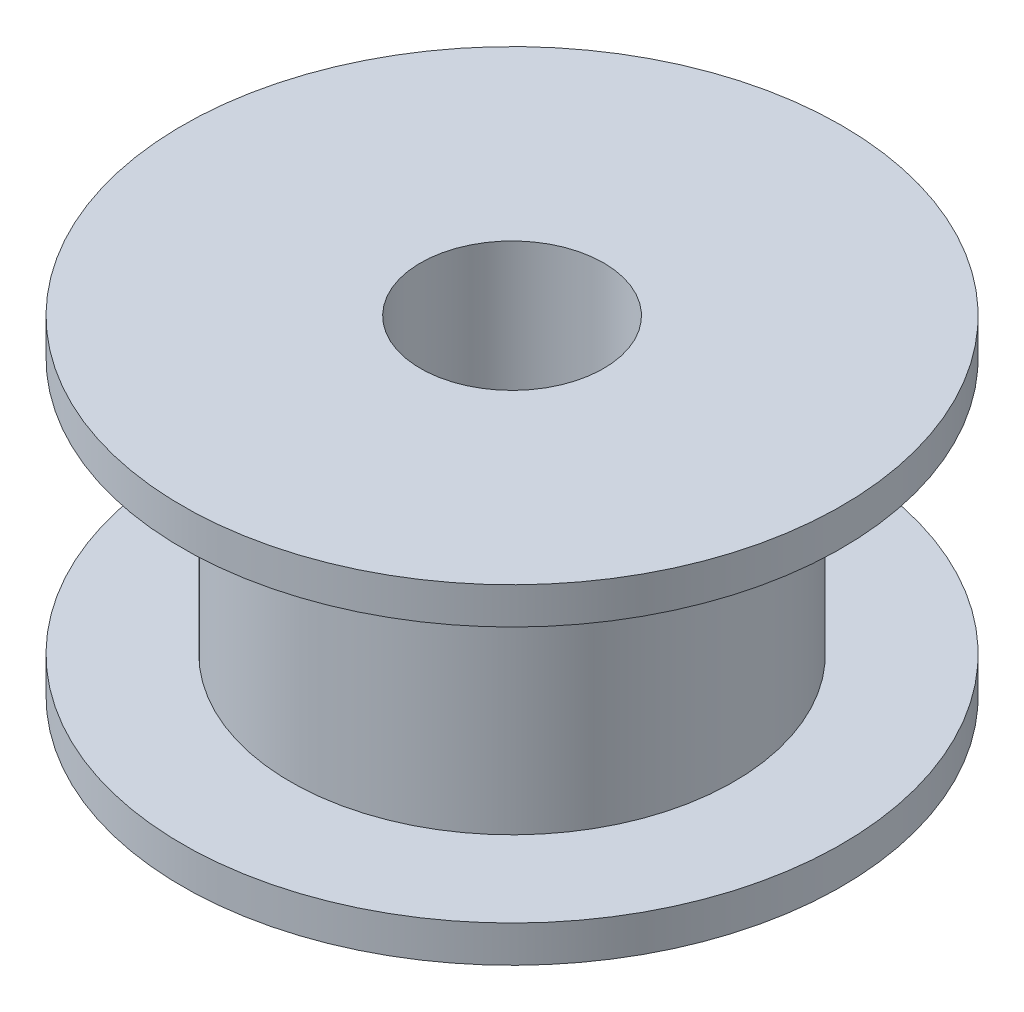
SolidWorks part; units mm, degrees
material "Chrome Stainless Steel"
ref_plane "Front Plane" through (0, 0, 0) normal (0, 0, 1) x (1, 0, 0)
ref_plane "Top Plane" through (0, 0, 0) normal (0, 1, 0) x (1, 0, 0)
ref_plane "Right Plane" through (0, 0, 0) normal (1, 0, 0) x (0, 0, -1)
sketch "Sketch1" plane through (0, 0, 0) normal (0, 0, 1) x (1, 0, 0)
  line L0 (-2.5, 0) -> (-9, 0)
  line L1 (-9, 0) -> (-9, 1)
  line L2 (-9, 1) -> (-6.05, 1)
  line L3 (-6.05, 1) -> (-6.05, 8)
  line L4 (-6.05, 8) -> (-9, 8)
  line L5 (-9, 8) -> (-9, 9)
  line L6 (-9, 9) -> (-2.5, 9)
  line L7 (-2.5, 9) -> (-2.5, 0)
  line L8 (0, 0) -> (0, 9) construction
  dimension "D1" = 9
  dimension "D2" = 7
  dimension "D3" = 2.5
  dimension "D4" = 9
  dimension "D5" = 6.05
revolve "Revolve1" add sketch "Sketch1" angle 360 about L8
